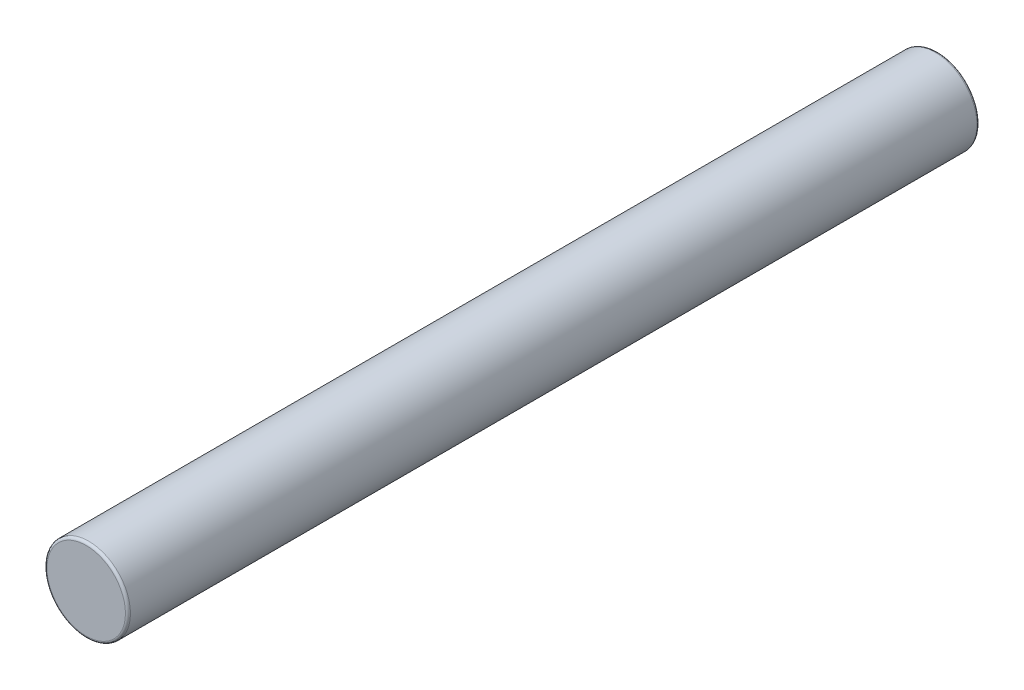
SolidWorks part; units mm, degrees
ref_plane "Płaszczyzna przednia" through (0, 0, 0) normal (0, 0, 1) x (1, 0, 0)
ref_plane "Płaszczyzna górna" through (0, 0, 0) normal (0, 1, 0) x (1, 0, 0)
ref_plane "Płaszczyzna prawa" through (0, 0, 0) normal (1, 0, 0) x (0, 0, -1)
sketch "Szkic1" plane through (0, 0, 0) normal (0, 0, 1) x (1, 0, 0)
  circle A0 centre (0, 0) radius 5
  dimension "D1" = 10
extrude "Dodanie-wyciągnięcie1" add sketch "Szkic1" along normal mid plane 102 contours A0
fillet "Zaokrąglenie1" radius 0.3 2 edges at (5, 0, -51) (5, 0, 51)
